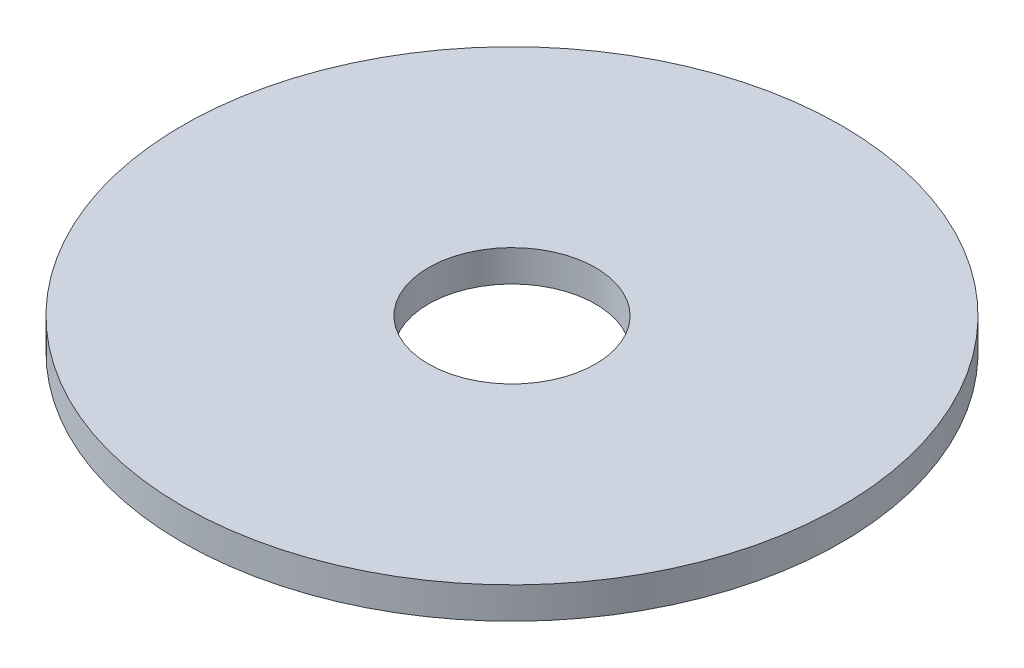
SolidWorks part; units mm, degrees
material "ASTM A36 Steel"
ref_plane "Front Plane" through (0, 0, 0) normal (0, 0, 1) x (1, 0, 0)
ref_plane "Top Plane" through (0, 0, 0) normal (0, 1, 0) x (1, 0, 0)
ref_plane "Right Plane" through (0, 0, 0) normal (1, 0, 0) x (0, 0, -1)
sketch "Sketch1" plane through (0, 0, 0) normal (0, 1, 0) x (1, 0, 0)
  circle A0 centre (0, 0) radius 104.55
  circle A1 centre (0, 0) radius 26.5
  dimension "D1" = 209.1
  dimension "D2" = 53
extrude "Boss-Extrude1" add sketch "Sketch1" along normal blind 10
